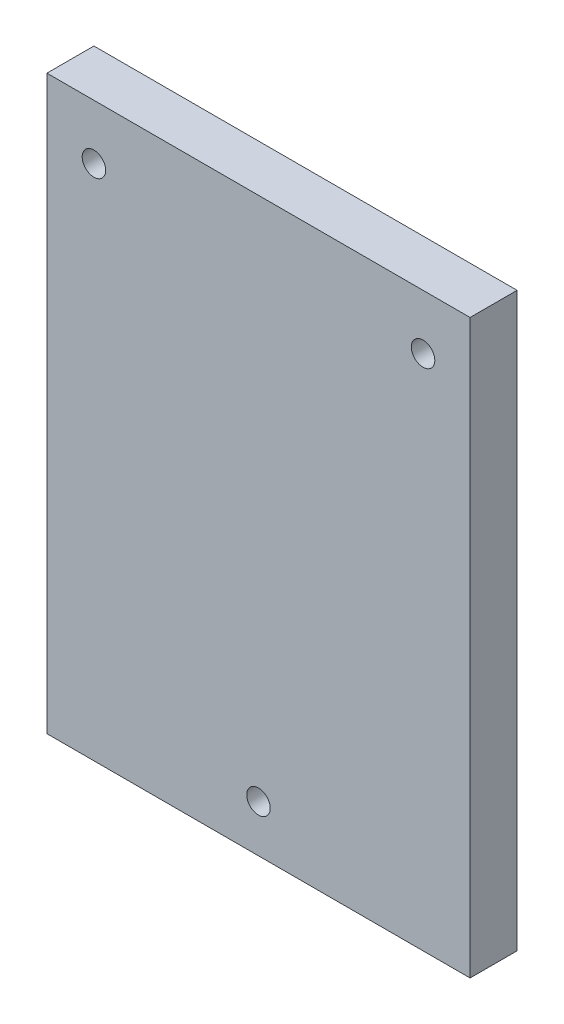
SolidWorks part; units mm, degrees
ref_plane "Спереди" through (0, 0, 0) normal (0, 0, 1) x (1, 0, 0)
ref_plane "Сверху" through (0, 0, 0) normal (0, 1, 0) x (1, 0, 0)
ref_plane "Справа" through (0, 0, 0) normal (1, 0, 0) x (0, 0, -1)
sketch "Эскиз1" plane through (0, 0, 0) normal (0, 0, 1) x (1, 0, 0)
  line L0 (44.275, -67) -> (44.275, 49933) construction
  line L1 (17.275, 0) -> (17.275, -73)
  line L2 (20.8625, 0) -> (10.8625, 0) construction
  line L3 (17.275, -73) -> (71.275, -73)
  line L4 (17.275, 0) -> (71.275, 0)
  line L5 (71.275, 0) -> (71.275, -73)
  circle A0 centre (44.275, -67) radius 1.5 construction
  circle A1 centre (65.275, -7) radius 1.5 construction
  circle A2 centre (23.275, -7) radius 1.5 construction
  circle A3 centre (44.275, -67) radius 1.5
  circle A4 centre (65.275, -7) radius 1.5
  circle A5 centre (23.275, -7) radius 1.5
  point P15 (71.9791, 0)
  point P20 (70.6045, -73)
  dimension "D1" = 6
  dimension "D2" = 6
extrude "Бобышка-Вытянуть1" add sketch "Эскиз1" along normal blind 6
